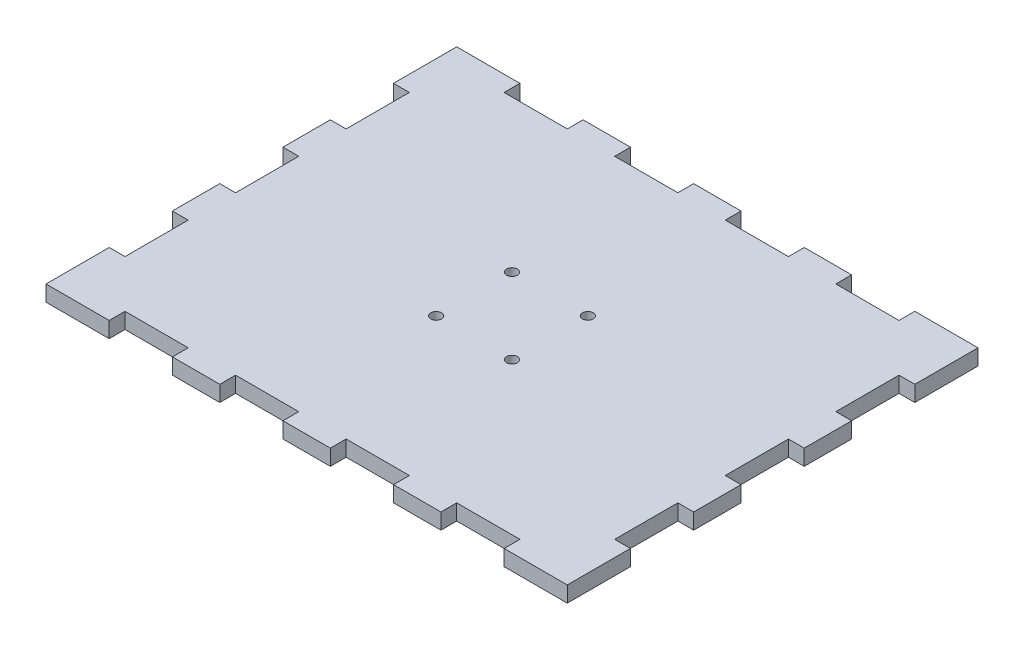
SolidWorks part; units mm, degrees
ref_plane "Front Plane" through (0, 0, 0) normal (0, 0, 1) x (1, 0, 0)
ref_plane "Top Plane" through (0, 0, 0) normal (0, 1, 0) x (1, 0, 0)
ref_plane "Right Plane" through (0, 0, 0) normal (1, 0, 0) x (0, 0, -1)
sketch "Sketch1" plane through (0, 0, 0) normal (0, 1, 0) x (1, 0, 0)
  line L0 (-80.6642, 0) -> (91.9196, 0) construction
  line L1 (0, -68.3473) -> (0, 67.4711) construction
  line L2 (-82.5, 60) -> (-82.5, 65)
  line L3 (-77.5, 60) -> (77.5, 60) construction
  line L4 (-77.5, 60) -> (-77.5, -60) construction
  line L5 (-77.5, -60) -> (77.5, -60) construction
  line L6 (77.5, 60) -> (77.5, -60) construction
  line L7 (-77.5, 60) -> (77.5, -60) construction
  line L8 (-77.5, -60) -> (77.5, 60) construction
  line L9 (-77.5, 65) -> (-62.5, 65)
  line L10 (-62.5, 65) -> (-62.5, 60)
  line L11 (-62.5, 60) -> (-42.5, 60)
  line L12 (-27.5, 60) -> (-7.5, 60)
  line L13 (-27.5, 65) -> (-27.5, 60)
  line L14 (-42.5, 65) -> (-27.5, 65)
  line L15 (-42.5, 60) -> (-42.5, 65)
  line L16 (7.5, 60) -> (27.5, 60)
  line L17 (7.5, 65) -> (7.5, 60)
  line L18 (-7.5, 65) -> (7.5, 65)
  line L19 (-7.5, 60) -> (-7.5, 65)
  line L20 (42.5, 60) -> (62.5, 60)
  line L21 (42.5, 65) -> (42.5, 60)
  line L22 (27.5, 65) -> (42.5, 65)
  line L23 (27.5, 60) -> (27.5, 65)
  line L24 (62.5, -60) -> (62.5, -65)
  line L25 (-82.5, 65) -> (-77.5, 65)
  line L26 (62.5, 65) -> (77.5, 65)
  line L27 (62.5, 60) -> (62.5, 65)
  line L28 (77.5, 60) -> (97.5, 60) [skipped]
  line L29 (62.5, -65) -> (77.5, -65)
  line L30 (77.5, 65) -> (82.5, 65)
  line L31 (27.5, -60) -> (27.5, -65)
  line L32 (27.5, -65) -> (42.5, -65)
  line L33 (42.5, -65) -> (42.5, -60)
  line L34 (42.5, -60) -> (62.5, -60)
  line L35 (-7.5, -60) -> (-7.5, -65)
  line L36 (-7.5, -65) -> (7.5, -65)
  line L37 (7.5, -65) -> (7.5, -60)
  line L38 (7.5, -60) -> (27.5, -60)
  line L39 (-42.5, -60) -> (-42.5, -65)
  line L40 (-42.5, -65) -> (-27.5, -65)
  line L41 (-27.5, -65) -> (-27.5, -60)
  line L42 (-27.5, -60) -> (-7.5, -60)
  line L43 (-62.5, -60) -> (-42.5, -60)
  line L44 (-62.5, -65) -> (-62.5, -60)
  line L45 (-77.5, -65) -> (-62.5, -65)
  line L46 (82.5, 65) -> (82.5, 60)
  line L47 (-82.5, -60) -> (-82.5, -65)
  line L48 (-82.5, 60) -> (-82.5, 45)
  line L49 (-82.5, 45) -> (-77.5, 45)
  line L50 (-77.5, 45) -> (-77.5, 25)
  line L51 (77.5, -45) -> (82.5, -45)
  line L52 (82.5, -45) -> (82.5, -60)
  line L53 (-82.5, -65) -> (-77.5, -65)
  line L54 (77.5, -10) -> (82.5, -10)
  line L55 (82.5, -10) -> (82.5, -25)
  line L56 (82.5, -25) -> (77.5, -25)
  line L57 (77.5, -25) -> (77.5, -45)
  line L58 (77.5, 25) -> (82.5, 25)
  line L59 (82.5, 25) -> (82.5, 10)
  line L60 (82.5, 10) -> (77.5, 10)
  line L61 (77.5, 10) -> (77.5, -10)
  line L62 (77.5, 45) -> (77.5, 25)
  line L63 (82.5, 45) -> (77.5, 45)
  line L64 (82.5, 60) -> (82.5, 45)
  line L65 (77.5, -65) -> (82.5, -65)
  line L66 (82.5, -65) -> (82.5, -60)
  line L67 (-77.5, 10) -> (-77.5, -10)
  line L68 (-82.5, 10) -> (-77.5, 10)
  line L69 (-82.5, 25) -> (-82.5, 10)
  line L70 (-77.5, 25) -> (-82.5, 25)
  line L71 (-77.5, -25) -> (-77.5, -45)
  line L72 (-82.5, -25) -> (-77.5, -25)
  line L73 (-82.5, -10) -> (-82.5, -25)
  line L74 (-77.5, -10) -> (-82.5, -10)
  line L77 (-82.5, -45) -> (-82.5, -60)
  line L78 (-77.5, -45) -> (-82.5, -45)
  line L79 (-97.5, 45) -> (-97.5, 25) [skipped]
  line L80 (-102.5, 45) -> (-97.5, 45) [skipped]
  line L81 (-102.5, 60) -> (-102.5, 45) [skipped]
  line L83 (-97.5, 10) -> (-97.5, -10) [skipped]
  line L84 (-102.5, 10) -> (-97.5, 10) [skipped]
  line L85 (-102.5, 25) -> (-102.5, 10) [skipped]
  line L87 (-97.5, -25) -> (-97.5, -45) [skipped]
  line L88 (-102.5, -25) -> (-97.5, -25) [skipped]
  line L89 (-102.5, -10) -> (-102.5, -25) [skipped]
  line L91 (-97.5, -60) -> (-97.5, -80) [skipped]
  line L92 (-102.5, -60) -> (-97.5, -60) [skipped]
  line L93 (-102.5, -45) -> (-102.5, -60) [skipped]
  line L95 (-77.5, -60) -> (-77.5, -80) [skipped]
  line L96 (77.5, 65) -> (77.5, 60) [skipped]
  line L97 (-82.5, -60) -> (-77.5, -60) [skipped]
  point P5 (0, 0)
  dimension "D2" = 155
  dimension "D3" = 5
  dimension "D4" = 2
  dimension "D5" = 4
extrude "Boss-Extrude1" add sketch "Sketch1" along normal blind 5
sketch "Sketch2" plane through (0, 5, 0) normal (0, 1, 0) x (1, 0, 0)
  line L5 (15, -15) -> (-15, 15) construction
  line L6 (15, 15) -> (-15, -15) construction
  circle A1 centre (-12, -12) radius 1.7
  circle A2 centre (-12, 12) radius 1.7
  circle A3 centre (12, 12) radius 1.7
  circle A4 centre (12, -12) radius 1.7
  point P0 (0, 0)
  point P6 (0, 0)
extrude "Cut-Extrude1" cut sketch "Sketch2" against normal blind 10
